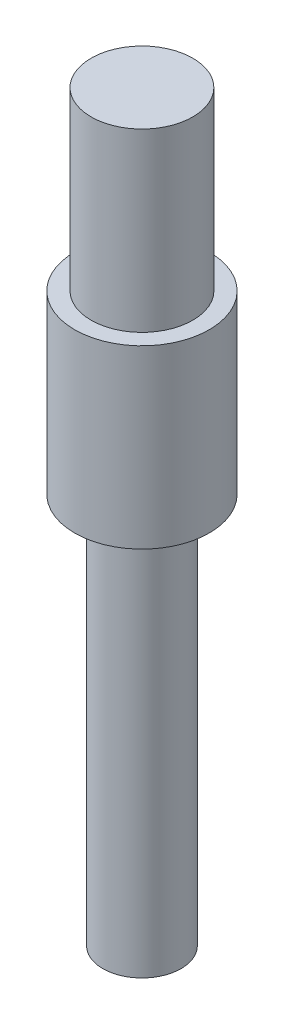
SolidWorks part; units mm, degrees
material "AISI 316 Annealed Stainless Steel Bar (SS)"
ref_plane "Front Plane" through (0, 0, 0) normal (0, 0, 1) x (1, 0, 0)
ref_plane "Top Plane" through (0, 0, 0) normal (0, 1, 0) x (1, 0, 0)
ref_plane "Right Plane" through (0, 0, 0) normal (1, 0, 0) x (0, 0, -1)
sketch "Sketch1" plane through (0, 0, 0) normal (0, 1, 0) x (1, 0, 0)
  circle A0 centre (0, 0) radius 6.35
  dimension "D1" = 12.7
extrude "Boss-Extrude1" add sketch "Sketch1" along normal blind 63.5
sketch "Sketch2" plane through (0, 63.5, 0) normal (0, 1, 0) x (1, 0, 0)
  circle A0 centre (0, 0) radius 10.922
  dimension "D1" = 21.844
extrude "Boss-Extrude2" add sketch "Sketch2" along normal blind 28.575
sketch "Sketch3" plane through (0, 92.075, 0) normal (0, 1, 0) x (1, 0, 0)
  circle A0 centre (0, 0) radius 8.255
  dimension "D1" = 16.51
extrude "Boss-Extrude3" add sketch "Sketch3" along normal blind 28.575
